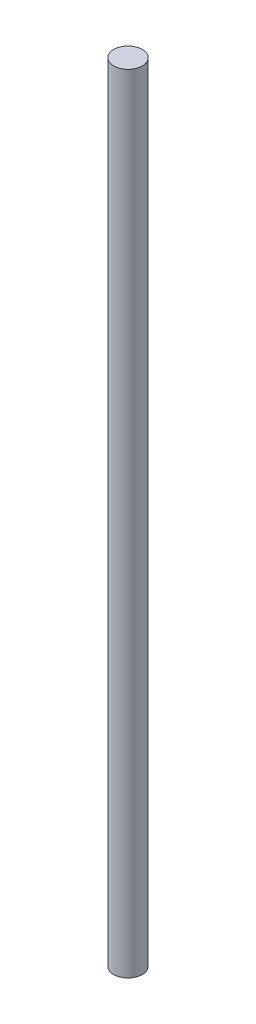
SolidWorks part; units mm, degrees
ref_plane "Alzado" through (0, 0, 0) normal (0, 0, 1) x (1, 0, 0)
ref_plane "Planta" through (0, 0, 0) normal (0, 1, 0) x (1, 0, 0)
ref_plane "Vista lateral" through (0, 0, 0) normal (1, 0, 0) x (0, 0, -1)
sketch "Croquis1" plane through (0, 0, 0) normal (0, 1, 0) x (1, 0, 0)
  circle A0 centre (0, 0) radius 3
  dimension "D1" = 6
extrude "Saliente-Extruir1" add sketch "Croquis1" along normal blind 165
